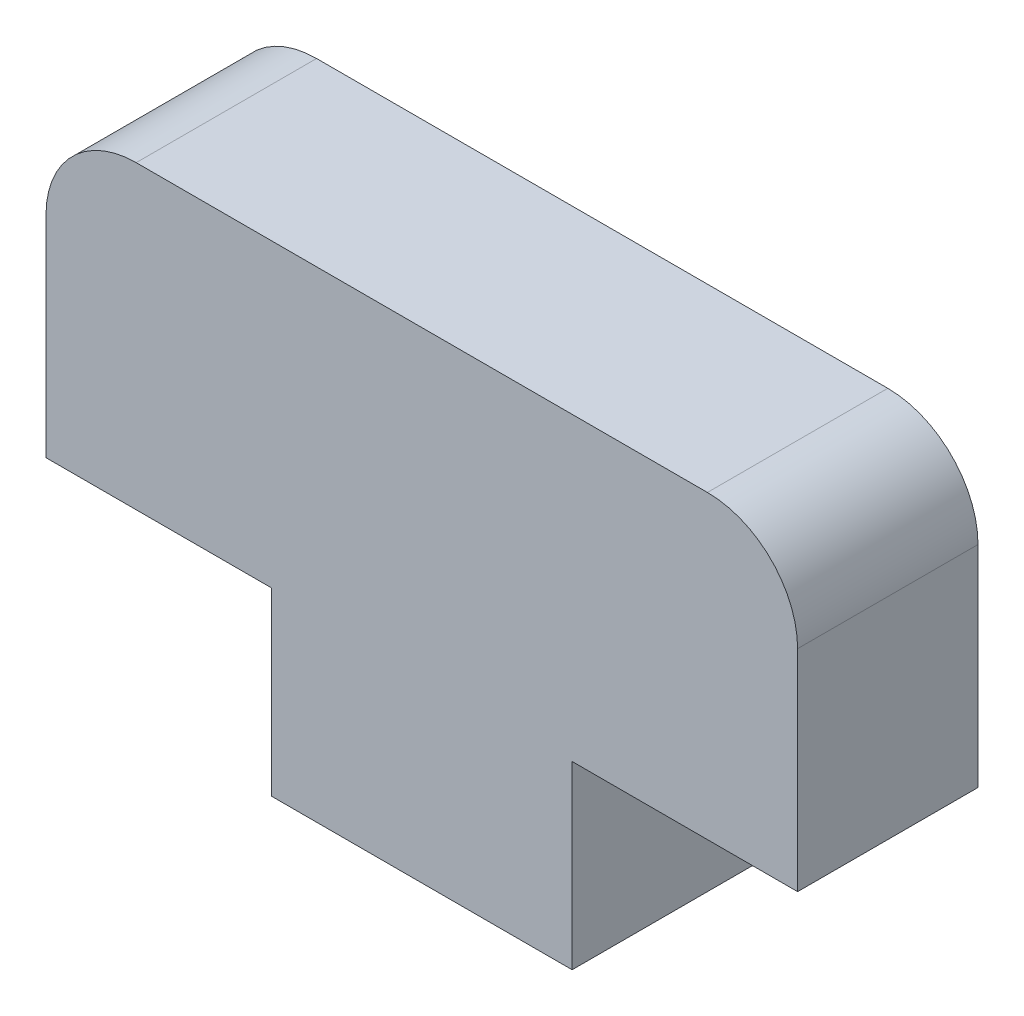
SolidWorks part; units mm, degrees
ref_plane "Plan de face" through (0, 0, 0) normal (0, 0, 1) x (1, 0, 0)
ref_plane "Plan de dessus" through (0, 0, 0) normal (0, 1, 0) x (1, 0, 0)
ref_plane "Plan de droite" through (0, 0, 0) normal (1, 0, 0) x (0, 0, -1)
sketch "Esquisse1" plane through (0, 0, 0) normal (0, 0, 1) x (1, 0, 0)
  line L0 (5, -5) -> (12.5, -5)
  line L1 (-12.5, 5) -> (12.5, 5)
  line L2 (-12.5, 5) -> (-12.5, -5)
  line L3 (-12.5, -5) -> (-5, -5)
  line L4 (12.5, 5) -> (12.5, -5)
  line L5 (-12.5, 5) -> (12.5, -5) construction
  line L6 (-12.5, -5) -> (12.5, 5) construction
  line L8 (-5, -5) -> (-5, -11)
  line L9 (-5, -11) -> (5, -11)
  line L10 (5, -5) -> (5, -11)
  point P0 (0, 0)
  dimension "D1" = 10
  dimension "D2" = 6
  dimension "D3" = 25
  dimension "D4" = 10
  dimension "D5" = 7.5
extrude "Boss.-Extru.1" add sketch "Esquisse1" along normal blind 6
fillet "Congé1" radius 3 2 edges at (12.5, 5, 3) (-12.5, 5, 3)
